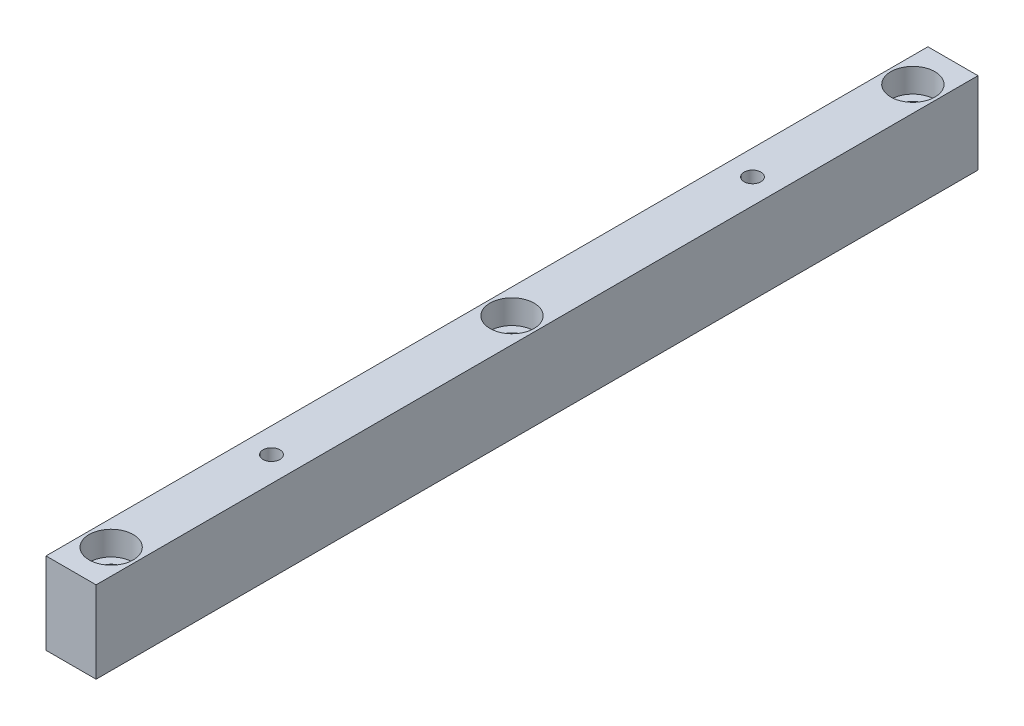
SolidWorks part; units mm, degrees
ref_plane "Front Plane" through (0, 0, 0) normal (0, 0, 1) x (1, 0, 0)
ref_plane "Top Plane" through (0, 0, 0) normal (0, 1, 0) x (1, 0, 0)
ref_plane "Right Plane" through (0, 0, 0) normal (1, 0, 0) x (0, 0, -1)
sketch "Sketch1" plane through (0, 0, 0) normal (0, 1, 0) x (1, 0, 0)
  line L1 (0, 0) -> (12.5, 0)
  line L2 (0, 0) -> (0, 220)
  line L3 (0, 220) -> (12.5, 220)
  line L4 (12.5, 0) -> (12.5, 220)
  dimension "D1" = 12.5
  dimension "D2" = 220
extrude "Bloco" add sketch "Sketch1" along normal blind 20.4
sketch "Posição - Furos" plane through (0, 20.4, 0) normal (0, 1, 0) x (1, 0, 0)
  line L0 (6.25, 0) -> (6.25, 220) construction
  line L1 (0, 0) -> (12.5, 0) construction
  line L2 (12.5, 220) -> (0, 220) construction
  circle A0 centre (6.25, 10) radius 3
  circle A1 centre (6.25, 110) radius 3
  circle A2 centre (6.25, 210) radius 3
  circle A3 centre (6.25, 170) radius 2.5
  circle A4 centre (6.25, 50) radius 2.5
  dimension "D1" = 5
  dimension "D2" = 6
  dimension "D3" = 100
  dimension "D4" = 100
  dimension "D5" = 60
  dimension "D6" = 60
hole_wizard "Rebaixo M6 - Passante" positions "Sketch5" profile "Sketch4" counterbore size "M6" standard "ANSI Metric" end condition through all
sketch "Sketch5" plane through (0, 20.4, 0) normal (0, 1, 0) x (1, 0, 0)
  point P0 (6.25, 10)
  point P3 (6.25, 110)
  point P6 (6.25, 210)
sketch "Sketch4" plane through (6.25, 20.4, -10) normal (1, 0, 0) x (0, 0, 1)
  line L0 (0, 0) -> (0, 20.4)
  line L1 (0, 20.4) -> (3.3, 20.4)
  line L3 (3.3, 20.4) -> (3.3, 6)
  line L4 (3.3, 6) -> (5.5, 6)
  line L5 (5.5, 6) -> (5.5, 0)
  line L7 (5.5, 0) -> (0, 0)
  line L11 (0, -6.35) -> (0, 107.95) construction
  dimension "Thru Hole Dia." = 6.6
  dimension "Thru Hole Depth" = 20.4
  dimension "C'Bore Dia." = 11
  dimension "C'Bore Depth" = 6
hole_wizard "Furo M5x0.8 - Passante" positions "Sketch6" profile "Sketch7" tap size "M5x0.8" standard "ANSI Metric" end condition through all
sketch "Sketch6" plane through (0, 20.4, 0) normal (0, 1, 0) x (1, 0, 0)
  point P0 (6.25, 50)
  point P3 (6.25, 170)
sketch "Sketch7" plane through (6.25, 20.4, -50) normal (1, 0, 0) x (0, 0, 1)
  line L0 (0, 0) -> (0, 20.4)
  line L1 (0, 20.4) -> (2.1, 20.4)
  line L2 (2.1, 20.4) -> (2.1, 0)
  line L5 (2.1, 0) -> (0, 0)
  line L11 (0, -6.35) -> (0, 107.95) construction
  dimension "Thru Tap Drill Dia." = 4.2
  dimension "Thru Tap Drill Depth" = 20.4
cosmetic thread "Hole Thread1"
cosmetic thread "Hole Thread2"
